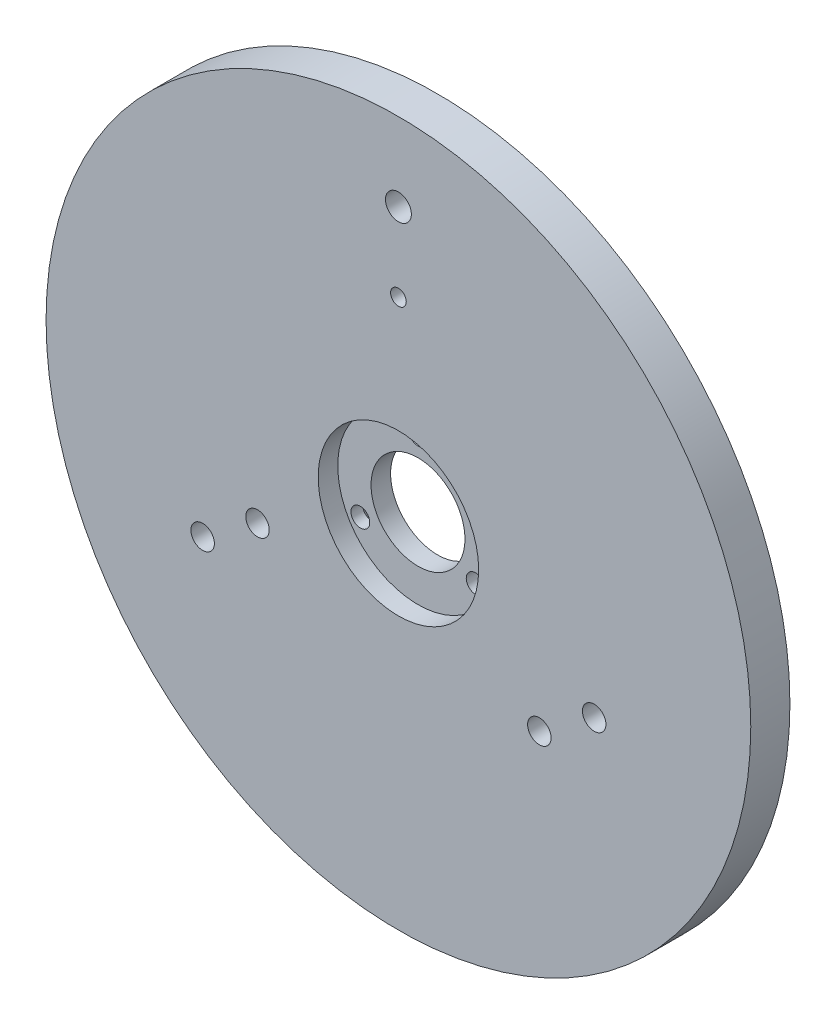
SolidWorks part; units mm, degrees
material "201 Annealed Stainless Steel (SS)"
ref_plane "Front Plane" through (0, 0, 0) normal (0, 0, 1) x (1, 0, 0)
ref_plane "Top Plane" through (0, 0, 0) normal (0, 1, 0) x (1, 0, 0)
ref_plane "Right Plane" through (0, 0, 0) normal (1, 0, 0) x (0, 0, -1)
sketch "Sketch1" plane through (0, 0, 39.5) normal (0, 0, 1) x (1, 0, 0)
  circle A0 centre (-40, 45) radius 45
  dimension "D1" = 90
extrude "Boss-Extrude1" add sketch "Sketch1" against normal blind 5
hole_wizard "Ø20.5 (20.5) Diameter Hole1" positions "Sketch3" profile "Sketch2" hole size "Ø20.5" standard "ANSI Metric"
sketch "Sketch3" plane through (0, 0, 39.5) normal (0, 0, 1) x (1, 0, 0)
  point P0 (-40, 45)
sketch "Sketch2" plane through (-40, 45, 39.5) normal (1, 0, 0) x (0, -1, 0)
  line L0 (0, 0) -> (0, 2.5)
  line L1 (0, 2.5) -> (10.25, 2.5)
  line L2 (10.25, 2.5) -> (10.25, 0)
  line L5 (10.25, 0) -> (0, 0)
  line L10 (0, 2.5) -> (-10.25, 2.5) construction
  line L11 (0, -6.35) -> (0, 107.95) construction
  dimension "Hole Dia." = 20.5
  dimension "Hole Depth" = 2.5
  dimension "Drill Angle" = 180
hole_wizard "Ø12.0 (12) Diameter Hole1" positions "Sketch5" profile "Sketch4" hole size "Ø12.0" standard "ANSI Metric"
sketch "Sketch5" plane through (0, 0, 39.5) normal (0, 0, 1) x (1, 0, 0)
  point P0 (-40, 45)
sketch "Sketch4" plane through (-40, 45, 39.5) normal (1, 0, 0) x (0, -1, 0)
  line L0 (0, 0) -> (0, 5)
  line L1 (0, 5) -> (6, 5)
  line L2 (6, 5) -> (6, 0)
  line L5 (6, 0) -> (0, 0)
  line L10 (0, 5) -> (-6, 5) construction
  line L11 (0, -6.35) -> (0, 107.95) construction
  dimension "Hole Dia." = 12
  dimension "Hole Depth" = 5
  dimension "Drill Angle" = 180
hole_wizard "CSK for M2 Flat Head Machine Screw1" positions "Sketch9" profile "Sketch10" countersink size "M2" standard "ANSI Metric"
sketch "Sketch9" plane through (0, 0, 34.5) normal (0, 0, 1) x (1, 0, 0)
  line L0 (-40, 45) -> (-40, 53.5) construction
  line L2 (-40, 45) -> (-32.6388, 40.75) construction
  circle A0 centre (-40, 45) radius 8.5 construction
  point P0 (-40, 53.5)
  point P4 (-32.6388, 40.75)
  point P32 (-47.3612, 40.75)
  dimension "D1" = 17
  dimension "D2" = 120
sketch "Sketch10" plane through (-40, 53.5, 34.5) normal (1, 0, 0) x (0, 1, 0)
  line L0 (0, 0) -> (0, 23.471)
  line L1 (0, 23.471) -> (1.2, 22.75)
  line L2 (1.2, 22.75) -> (1.2, 1)
  line L3 (1.2, 1) -> (2.2, 0)
  line L5 (2.2, 0) -> (0, 0)
  line L6 (-1.2, 1) -> (-2.2, 0) construction
  line L10 (0, 23.471) -> (-1.2, 22.75) construction
  line L11 (0, -6.35) -> (0, 107.95) construction
  dimension "Hole Dia." = 2.4
  dimension "Hole Depth" = 22.75
  dimension "Near C'Sink Dia." = 4.4
  dimension "Near C'Sink Angle" = 90
  dimension "Drill Angle" = 118
hole_wizard "M4x0.7 Tapped Hole1" positions "Sketch14" profile "Sketch13" tap size "M4x0.7" standard "ANSI Metric" end condition through all
sketch "Sketch14" plane through (0, 0, 39.5) normal (0, 0, 1) x (1, 0, 0)
  point P0 (-40, 80)
sketch "Sketch13" plane through (-40, 80, 39.5) normal (1, 0, 0) x (0, -1, 0)
  line L0 (0, 0) -> (0, 5)
  line L1 (0, 5) -> (1.65, 5)
  line L2 (1.65, 5) -> (1.65, 0)
  line L5 (1.65, 0) -> (0, 0)
  line L11 (0, -6.35) -> (0, 107.95) construction
  dimension "Thru Tap Drill Dia." = 3.3
  dimension "Thru Tap Drill Depth" = 5
cosmetic thread "Hole Thread3" parameters "D2"=4
sketch "Sketch15" plane through (0, 0, 39.5) normal (0, 0, 1) x (1, 0, 0)
  circle A0 centre (-58, 36) radius 1.5
  circle A1 centre (-65, 31) radius 1.5
  circle A2 centre (-15, 36) radius 1.5
  circle A3 centre (-22, 31) radius 1.5
  dimension "D1" = 3
extrude "M3 Tapped Hole" cut sketch "Sketch15" against normal through all
sketch "Sketch16" plane through (0, 0, 39.5) normal (0, 0, 1) x (1, 0, 0)
  line L0 (-45, 70) -> (-35, 70) construction
  circle A0 centre (-40, 70) radius 1
extrude "2mm Pin" cut sketch "Sketch16" against normal through all
